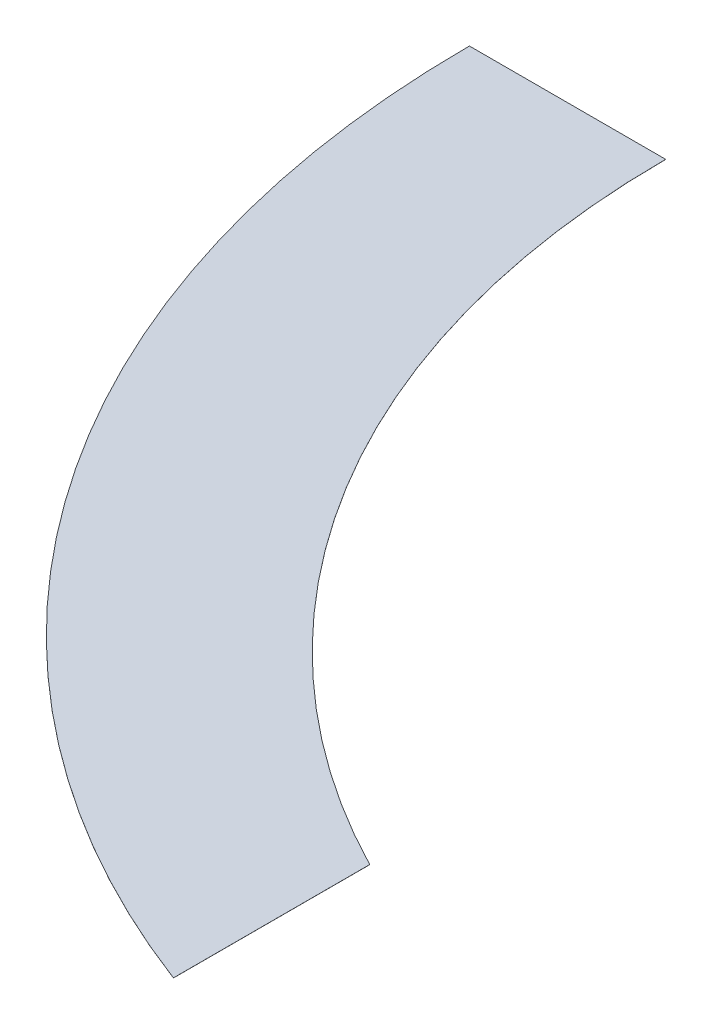
SolidWorks part; units mm, degrees
ref_plane "Plano frontal" through (0, 0, 0) normal (0, 0, 1) x (1, 0, 0)
ref_plane "Plano superior" through (0, 0, 0) normal (0, 1, 0) x (1, 0, 0)
ref_plane "Plano direito" through (0, 0, 0) normal (1, 0, 0) x (0, 0, -1)
sketch "Esboço1" plane through (0, 0, 0) normal (0, 1, 0) x (1, 0, 0)
  line L0 (-1093, 595.536) -> (-1073, 595.536)
  line L1 (0, 0) -> (18.9344, 0)
  line L2 (0, 0) -> (0, 766.8662)
  line L3 (0, 766.8662) -> (18.9344, 766.8662)
  line L4 (18.9344, 0) -> (18.9344, 766.8662)
  line L5 (-381.6968, 766.8662) -> (-362.7624, 766.8662)
  line L6 (-381.6968, 766.8662) -> (-381.6968, 345.536)
  line L7 (-381.6968, 345.536) -> (-362.7624, 345.536)
  line L8 (-362.7624, 766.8662) -> (-362.7624, 345.536)
  line L9 (-858.9344, 645.536) -> (-840, 645.536)
  line L10 (-858.9344, 645.536) -> (-858.9344, 345.536)
  line L11 (-858.9344, 345.536) -> (-840, 345.536)
  line L12 (-840, 645.536) -> (-840, 345.536)
  line L13 (-853.5858, 925.2213) -> (-1253.5858, 925.2213)
  line L14 (-853.5858, 925.2213) -> (-853.5858, 945.2213)
  line L15 (-853.5858, 945.2213) -> (-1253.5858, 945.2213)
  line L16 (-1253.5858, 925.2213) -> (-1253.5858, 945.2213)
  line L17 (-1093, 595.536) -> (-1093, 195.536)
  line L18 (-1093, 195.536) -> (-1073, 195.536)
  line L19 (-1073, 595.536) -> (-1073, 195.536)
  line L21 (-858.9344, 427.7897) -> (-1250.0103, 427.7897)
  line L23 (-858.9344, 407.7897) -> (-1250.0103, 407.7897)
  line L24 (-1250.0103, 427.7897) -> (-1250.0103, 407.7897)
  line L33 (-1439.6613, 239.7512) -> (-1560.0448, 239.7512)
  line L34 (-1439.6613, 239.7512) -> (-1439.6613, 219.7512)
  line L35 (-1439.6613, 219.7512) -> (-1560.0448, 219.7512)
  line L36 (-1560.0448, 239.7512) -> (-1560.0448, 219.7512)
  line L37 (-1627.2015, 576.144) -> (-1607.2015, 576.144)
  line L38 (-1627.2015, 576.144) -> (-1627.2015, 317.0654)
  line L39 (-1627.2015, 317.0654) -> (-1607.2015, 317.0654)
  line L40 (-1607.2015, 576.144) -> (-1607.2015, 317.0654)
  line L41 (-1627.2015, 769.6927) -> (-1607.2015, 769.6927)
  line L42 (-1627.2015, 769.6927) -> (-1627.2015, 1019.6927)
  line L43 (-1627.2015, 1019.6927) -> (-1607.2015, 1019.6927)
  line L44 (-1607.2015, 769.6927) -> (-1607.2015, 1019.6927)
  line L45 (-1736.4022, 241.2781) -> (-1736.4022, 221.2781)
  line L46 (-1803.5589, 318.5923) -> (-1783.5589, 318.5923)
  arc A6 (-381.6968, 766.8662) -> (18.9344, 766.8662) centre (-181.3812, 766.8662) cw
  arc A7 (-362.7624, 766.8662) -> (0, 766.8662) centre (-181.3812, 766.8662) cw
  arc A8 (-362.7624, 345.536) -> (-858.9344, 345.536) centre (-610.8484, 345.536) cw
  arc A9 (-381.6968, 345.536) -> (-840, 345.536) centre (-610.8484, 345.536) cw
  arc A10 (-840, 645.536) -> (-803.6955, 702.0415) centre (-777.8744, 645.536) cw
  arc A11 (-803.6955, 702.0415) -> (-853.5858, 945.2213) centre (-856.6336, 817.8884) ccw
  arc A12 (-858.9344, 645.536) -> (-814.4955, 717.9247) centre (-777.7563, 645.536) cw
  arc A13 (-814.4955, 717.9247) -> (-853.5858, 925.2213) centre (-864.2122, 815.8835) ccw
  arc A14 (-1093, 595.536) -> (-1188.5366, 677.9223) centre (-1176.2913, 595.536) ccw
  arc A15 (-1188.5366, 677.9223) -> (-1354.3411, 742.8189) centre (-1214.8489, 854.9525) cw
  arc A16 (-1354.3411, 742.8189) -> (-1253.5858, 945.2213) centre (-1257.3278, 820.805) cw
  arc A17 (-1073, 595.536) -> (-1188.5366, 698.0004) centre (-1176.2038, 595.536) ccw
  arc A18 (-1188.5366, 698.0004) -> (-1341.8208, 766.8662) centre (-1207.9995, 859.705) cw
  arc A19 (-1341.8208, 766.8662) -> (-1253.5858, 925.2213) centre (-1258.876, 824.4093) cw
  arc A22 (-1368.7558, 309.7722) -> (-1439.6613, 219.7512) centre (-1474.849, 320.402) cw
  arc A23 (-1388.5562, 309.7722) -> (-1439.6613, 239.7512) centre (-1477.6183, 321.1143) cw
  arc A24 (-1388.5562, 309.7722) -> (-1250.0103, 427.7897) centre (-1254.4723, 292.6965) cw
  arc A25 (-1607.2015, 317.0654) -> (-1560.0448, 239.7512) centre (-1520.2441, 317.0654) ccw
  arc A26 (-1627.2015, 317.0654) -> (-1560.0448, 219.7512) centre (-1523.1159, 317.0654) ccw
  arc A27 (-1368.7558, 309.7722) -> (-1250.0103, 407.7897) centre (-1259.9289, 298.8686) cw
  arc A28 (-1783.5589, 318.5923) -> (-1736.4022, 241.2781) centre (-1696.6015, 318.5923) ccw
  arc A29 (-1803.5589, 318.5923) -> (-1736.4022, 221.2781) centre (-1699.4733, 318.5923) ccw
extrude "Ressalto-extrusão16" add sketch "Esboço1" along normal blind 0.01 contours A29 L45 A28 L46
